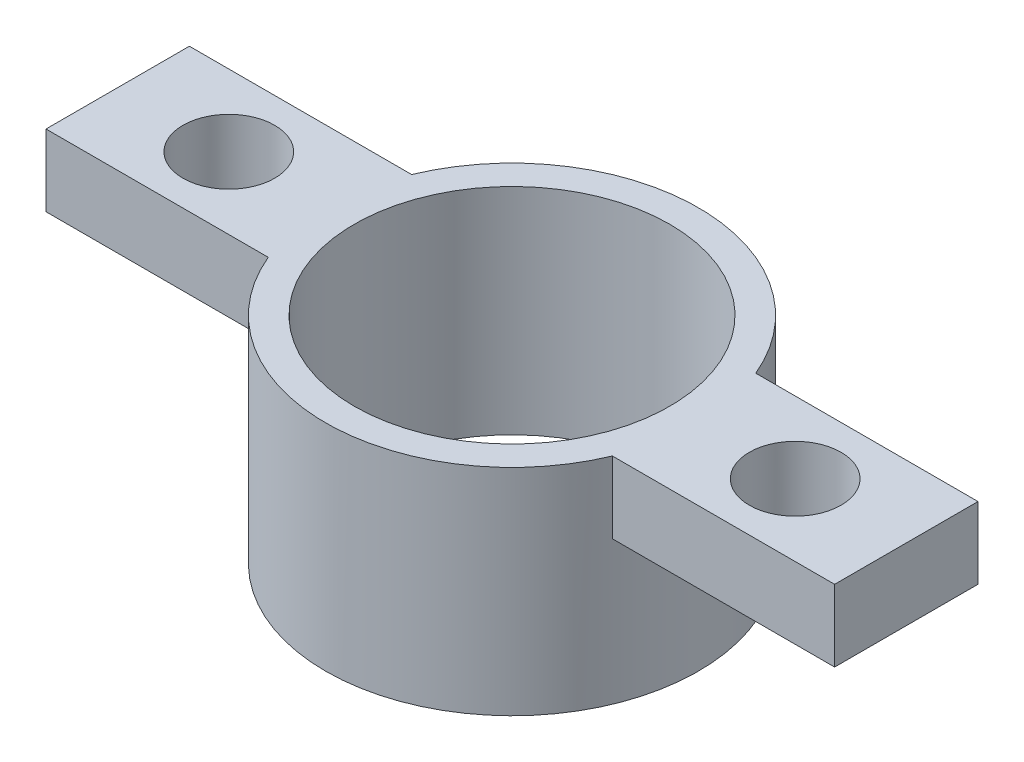
SolidWorks part; units mm, degrees
ref_plane "Front" through (0, 0, 0) normal (0, 0, 1) x (1, 0, 0)
ref_plane "Top" through (0, 0, 0) normal (0, 1, 0) x (1, 0, 0)
ref_plane "Right" through (0, 0, 0) normal (1, 0, 0) x (0, 0, -1)
sketch "Sketch1" plane through (0, 0, 0) normal (0, 1, 0) x (1, 0, 0)
  circle A0 centre (0, 0) radius 5.5
  circle A1 centre (0, 0) radius 6.5
  dimension "D1" = 11
  dimension "D2" = 13
extrude "Boss-Extrude1" add sketch "Sketch1" along normal blind 7.5
sketch "Sketch2" plane through (0, 7.5, 0) normal (0, 1, 0) x (1, 0, 0)
  line L0 (-13.75, 2.5) -> (-6, 2.5)
  line L1 (-13.75, -2.5) -> (13.75, -2.5) construction
  line L2 (-13.75, -2.5) -> (-13.75, 2.5)
  line L3 (-13.75, 2.5) -> (13.75, 2.5) construction
  line L4 (13.75, -2.5) -> (13.75, 2.5)
  line L5 (-13.75, -2.5) -> (13.75, 2.5) construction
  line L6 (-13.75, 2.5) -> (13.75, -2.5) construction
  line L7 (-13.75, -2.5) -> (-6, -2.5)
  line L8 (6, 2.5) -> (13.75, 2.5)
  line L9 (6, -2.5) -> (13.75, -2.5)
  arc A0 (-6, -2.5) -> (-6, 2.5) centre (0, 0) cw
  circle A1 centre (0, 0) radius 6.5 construction
  arc A2 (6, 2.5) -> (6, -2.5) centre (0, 0) cw
  point P0 (0, 0)
  dimension "D1" = 5
  dimension "D2" = 27.5
extrude "Boss-Extrude2" add sketch "Sketch2" against normal blind 2.5
sketch "Sketch3" plane through (0, 5, 0) normal (0, -1, 0) x (1, 0, 0)
  line L0 (9.875, -2.5) -> (9.875, 2.5) construction
  line L1 (13.75, -2.5) -> (6, -2.5) construction
  line L2 (6, 2.5) -> (13.75, 2.5) construction
  line L3 (-9.875, -2.5) -> (-9.875, 2.5) construction
  line L4 (-6, -2.5) -> (-13.75, -2.5) construction
  line L5 (-13.75, 2.5) -> (-6, 2.5) construction
  point P6 (9.875, 0)
  point P13 (-9.875, 0)
hole_wizard "M3 Clearance Hole1" positions "3DSketch1" profile "Sketch4" hole size "M3" standard "ANSI Metric"
sketch3d "3DSketch1"
  point P0 (9.875, 5, 0)
  point P3 (-9.875, 5, 0)
sketch "Sketch4" plane through (9.875, 5, 0) normal (1, 0, 0) x (0, 0, -1)
  line L0 (0, 0) -> (0, 5.9614)
  line L1 (0, 5.9614) -> (1.6, 5)
  line L2 (1.6, 5) -> (1.6, 0)
  line L5 (1.6, 0) -> (0, 0)
  line L10 (0, 5.9614) -> (-1.6, 5) construction
  line L11 (0, -6.35) -> (0, 107.95) construction
  dimension "Hole Dia." = 3.2
  dimension "Hole Depth" = 5
  dimension "Drill Angle" = 118
